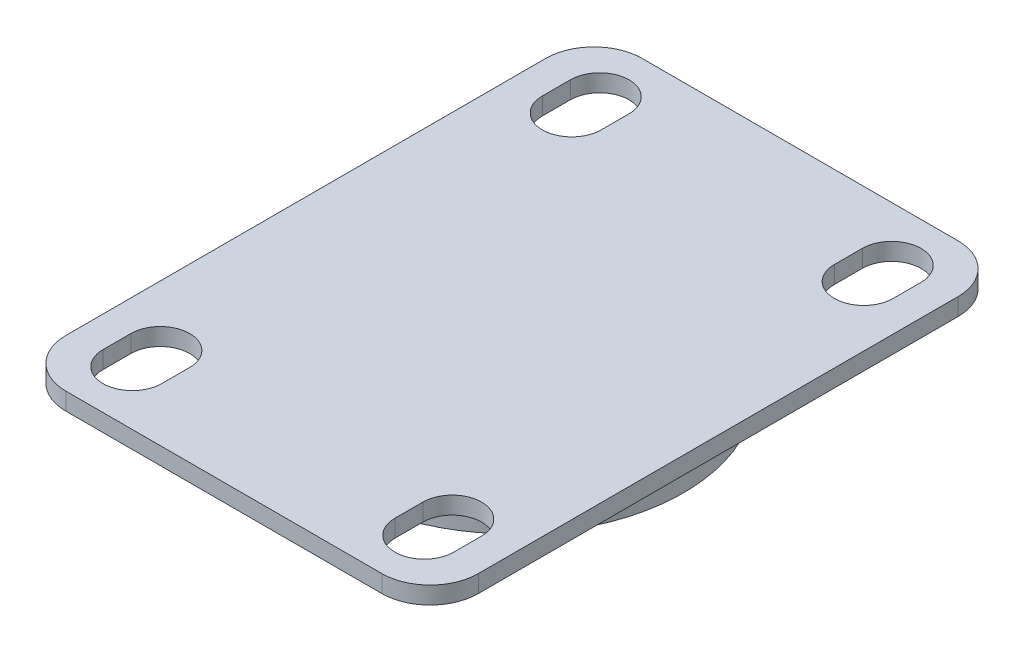
SolidWorks part; units mm, degrees
ref_plane "Front Plane" through (0, 0, 0) normal (0, 0, 1) x (1, 0, 0)
ref_plane "Top Plane" through (0, 0, 0) normal (0, 1, 0) x (1, 0, 0)
ref_plane "Right Plane" through (0, 0, 0) normal (1, 0, 0) x (0, 0, -1)
sketch "Sketch1" plane through (0, 0, 0) normal (0, 1, 0) x (1, 0, 0)
  line L0 (0, 0) -> (0, 18.2619) construction
  line L1 (-16.4, -29.9) -> (16.4, -29.9)
  line L2 (-21.4, -24.9) -> (-21.4, 24.9)
  line L3 (-16.4, 29.9) -> (16.4, 29.9)
  line L4 (21.4, -24.9) -> (21.4, 24.9)
  line L5 (-21.4, -29.9) -> (21.4, 29.9) construction
  line L6 (-21.4, 29.9) -> (21.4, -29.9) construction
  line L7 (0, 0) -> (-39.681, 0) construction
  line L8 (-15.15, 24.25) -> (-15.15, 21.35) construction
  line L9 (-12.1, 24.25) -> (-12.1, 21.35)
  line L10 (-18.2, 24.25) -> (-18.2, 21.35)
  line L11 (-15.15, -24.25) -> (-15.15, -21.35) construction
  line L12 (-12.1, -24.25) -> (-12.1, -21.35)
  line L13 (-18.2, -24.25) -> (-18.2, -21.35)
  line L14 (15.15, 24.25) -> (15.15, 21.35) construction
  line L15 (12.1, 24.25) -> (12.1, 21.35)
  line L16 (18.2, 24.25) -> (18.2, 21.35)
  line L17 (15.15, -24.25) -> (15.15, -21.35) construction
  line L18 (12.1, -24.25) -> (12.1, -21.35)
  line L19 (18.2, -24.25) -> (18.2, -21.35)
  arc A0 (-12.1, 24.25) -> (-18.2, 24.25) centre (-15.15, 24.25) ccw
  arc A1 (-18.2, 21.35) -> (-12.1, 21.35) centre (-15.15, 21.35) ccw
  arc A2 (-12.1, -24.25) -> (-18.2, -24.25) centre (-15.15, -24.25) cw
  arc A3 (-18.2, -21.35) -> (-12.1, -21.35) centre (-15.15, -21.35) cw
  arc A4 (12.1, 24.25) -> (18.2, 24.25) centre (15.15, 24.25) cw
  arc A5 (18.2, 21.35) -> (12.1, 21.35) centre (15.15, 21.35) cw
  arc A6 (12.1, -24.25) -> (18.2, -24.25) centre (15.15, -24.25) ccw
  arc A7 (18.2, -21.35) -> (12.1, -21.35) centre (15.15, -21.35) ccw
  arc A8 (-16.4, -29.9) -> (-21.4, -24.9) centre (-16.4, -24.9) cw
  arc A9 (21.4, -24.9) -> (16.4, -29.9) centre (16.4, -24.9) cw
  arc A10 (21.4, 24.9) -> (16.4, 29.9) centre (16.4, 24.9) ccw
  arc A11 (-21.4, 24.9) -> (-16.4, 29.9) centre (-16.4, 24.9) cw
  point P0 (0, 0)
  point P12 (-15.15, 22.8)
  point P17 (-15.15, 27.3)
  point P18 (-15.15, 18.3)
  point P22 (-15.15, -22.8)
  point P29 (15.15, 22.8)
  point P36 (15.15, -22.8)
  dimension "D7" = 5
  dimension "D1" = 59.8
  dimension "D2" = 42.8
  dimension "D3" = 9
  dimension "D4" = 6.1
  dimension "D5" = 3.2
  dimension "D6" = 2.6
extrude "Boss-Extrude1" add sketch "Sketch1" along normal blind 1.8
sketch "Sketch2" plane through (0, 0, 0) normal (0, -1, 0) x (1, 0, 0)
  circle A0 centre (0, 0) radius 15.95
  point P3 (0, 15.95)
  dimension "D1" = 31.9
ref_plane "Plane1" through (0, -3.2, 0) normal (0, -1, 0) x (-1, 0, 0)
sketch "Sketch3" plane through (0, -3.2, 0) normal (0, -1, 0) x (-1, 0, 0)
  circle A0 centre (0, 0) radius 17.8
  point P3 (0, -17.8)
  dimension "D1" = 35.6
loft "Loft1" add profiles "Sketch3", "Sketch2"
sketch "Sketch4" plane through (0, -3.2, 0) normal (0, -1, 0) x (1, 0, 0)
  circle A1 centre (0, 0) radius 17.8
  circle A2 centre (0, 0) radius 17.8
  dimension "D1" = 0
extrude "Boss-Extrude2" add sketch "Sketch4" along normal blind 2 separate body
equation "\"rect_breadth\"= 42.8"
equation "\"ract_len\"= 59.8"
equation "\"slot_len_gap\"= 2.6"
equation "\"slot_breadth_gap\"= 3.2"
equation "\"slot_t\"= 6.1mm"
equation "\"slot_circ_to_circ\"= 9"
equation "\"rect_bot_circ\"= 31.9"
equation "\"rect_top_circ\"= 35.6"
equation "\"loft_ht\"= 3.2"
equation "\"rect_top_circ_ht\"= 2"
equation "\"cylinder_t\"= 1.8"
equation "\"D2@Sketch1\"=\"rect_breadth\""
equation "\"D4@Sketch1\"=\"slot_t\""
equation "\"D3@Sketch1\"=\"slot_circ_to_circ\""
equation "\"D6@Sketch1\"=\"slot_len_gap\""
equation "\"D5@Sketch1\"=\"slot_breadth_gap\""
equation "\"D1@Boss-Extrude1\"=\"cylinder_t\""
equation "\"D1@Sketch2\"=\"rect_bot_circ\""
equation "\"D1@Sketch3\"=\"rect_top_circ\""
equation "\"D1@Boss-Extrude2\"=\"rect_top_circ_ht\""
